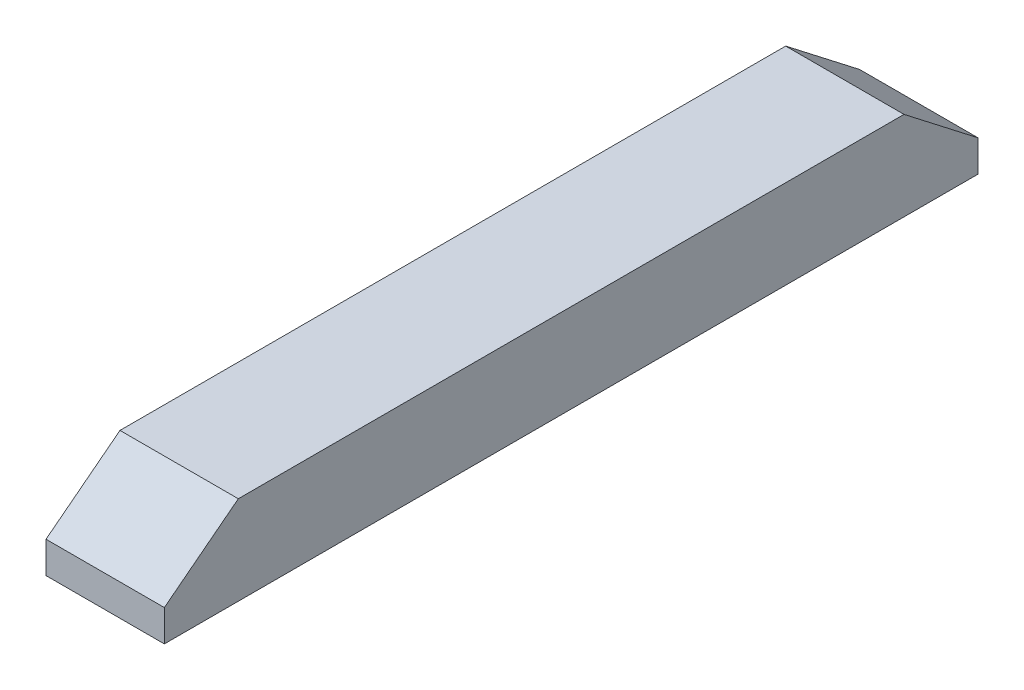
SolidWorks part; units mm, degrees
material "Oak"
ref_plane "Front Plane" through (0, 0, 0) normal (0, 0, 1) x (1, 0, 0)
ref_plane "Top Plane" through (0, 0, 0) normal (0, 1, 0) x (1, 0, 0)
ref_plane "Right Plane" through (0, 0, 0) normal (1, 0, 0) x (0, 0, -1)
sketch "Sketch2" plane through (0, 0, 0) normal (0, 0, 1) x (1, 0, 0)
  line L1 (-40, 30) -> (40, 30)
  line L2 (-40, 30) -> (-40, -30)
  line L3 (-40, -30) -> (40, -30)
  line L4 (40, 30) -> (40, -30)
  line L5 (-40, 30) -> (40, -30) construction
  line L6 (-40, -30) -> (40, 30) construction
  point P0 (0, 0)
  dimension "D1" = 80
  dimension "D2" = 60
extrude "Boss-Extrude1" add sketch "Sketch2" along normal blind 550
sketch "Sketch3" plane through (40, 0, 0) normal (1, 0, 0) x (0, 0, -1)
  line L0 (-50, 30) -> (0, -8.6994)
  line L1 (-550, 30) -> (0, 30) construction
  line L2 (0, -30) -> (0, 30) construction
  line L3 (0, -30) -> (-50, -30)
  line L4 (-550, -30) -> (0, -30) construction
  line L5 (-50, -30) -> (-50, 30)
  line L6 (-550, -8.6994) -> (-500, 30)
  line L7 (-550, -30) -> (-550, 30) construction
  line L8 (-500, 30) -> (-500, -30)
  line L9 (-500, -30) -> (-550, -30)
  line L10 (-550, -30) -> (-550, -8.6994)
  line L11 (0, -8.6994) -> (0, -30)
  dimension "D1" = 50
  dimension "D2" = 50
sketch "Sketch4" plane through (40, 0, 0) normal (1, 0, 0) x (0, 0, -1)
  line L0 (-550, 30) -> (-550, -8.6994)
  line L1 (-550, -8.6994) -> (-500, 30)
  line L2 (-500, 30) -> (-550, 30)
  line L3 (-50, 30) -> (0, -8.6994)
  line L4 (0, -8.6994) -> (0, 30)
  line L5 (0, 30) -> (-50, 30)
extrude "Cut-Extrude3" cut sketch "Sketch4" against normal blind 80
